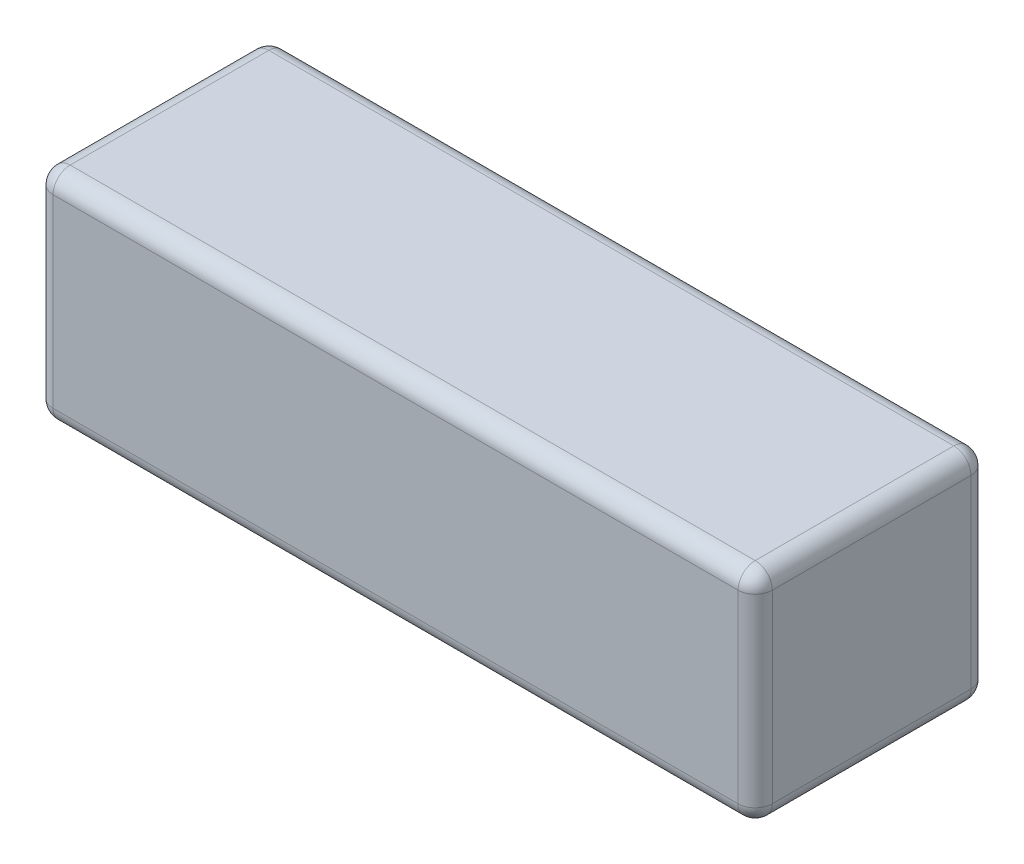
SolidWorks part; units mm, degrees
ref_plane "Front Plane" through (0, 0, 0) normal (0, 0, 1) x (1, 0, 0)
ref_plane "Top Plane" through (0, 0, 0) normal (0, 1, 0) x (1, 0, 0)
ref_plane "Right Plane" through (0, 0, 0) normal (1, 0, 0) x (0, 0, -1)
sketch "Sketch1" plane through (0, 0, 0) normal (0, 1, 0) x (1, 0, 0)
  line L1 (0, 0) -> (105, 0)
  line L2 (0, 0) -> (0, 34)
  line L3 (0, 34) -> (105, 34)
  line L4 (105, 0) -> (105, 34)
  dimension "D1" = 105
  dimension "D2" = 34
extrude "Boss-Extrude1" add sketch "Sketch1" along normal blind 32
fillet "Fillet1" radius 2.5 12 edges at (52.5, 0, 0) (105, 0, -17) (52.5, 0, -34) (0, 0, -17) (52.5, 32, -34) (105, 32, -17) (52.5, 32, 0) (0, 32, -17) (0, 16, 0) (0, 16, -34) (105, 16, 0) (105, 16, -34)
